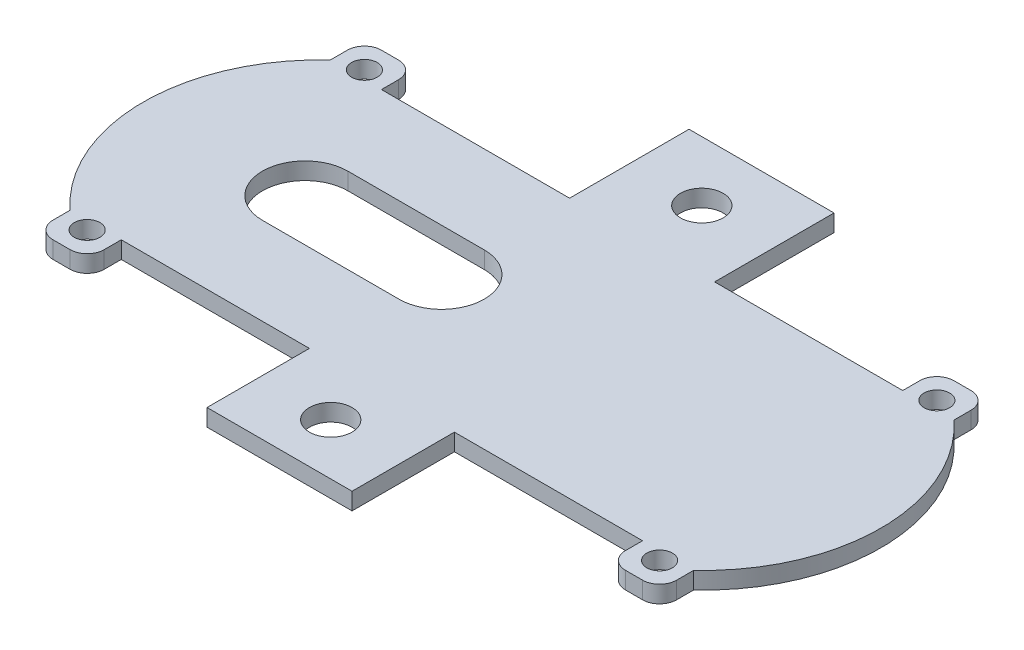
SolidWorks part; units mm, degrees
ref_plane "Front Plane" through (0, 0, 0) normal (0, 0, 1) x (1, 0, 0)
ref_plane "Top Plane" through (0, 0, 0) normal (0, 1, 0) x (1, 0, 0)
ref_plane "Right Plane" through (0, 0, 0) normal (1, 0, 0) x (0, 0, -1)
sketch "Sketch1" plane through (0, 0, 0) normal (0, 1, 0) x (1, 0, 0)
  line L0 (8.6417, -21.9202) -> (8.6417, -9.9202)
  line L1 (8.6417, -9.9202) -> (30.694, -9.9202)
  line L2 (30.694, -9.9202) -> (30.694, -13.9202)
  line L3 (30.694, -13.9202) -> (36.694, -13.9202)
  line L4 (36.694, -13.9202) -> (36.694, -9.9202)
  line L5 (36.694, 20.5798) -> (36.694, 24.5798)
  line L6 (36.694, 24.5798) -> (30.694, 24.5798)
  line L7 (30.694, 24.5798) -> (30.694, 20.5798)
  line L8 (30.694, 20.5798) -> (8.6417, 20.5798)
  line L9 (8.6417, 20.5798) -> (8.6417, 34.5798)
  line L10 (8.6417, 34.5798) -> (-8.3583, 34.5798)
  line L11 (-8.3583, 34.5798) -> (-8.3583, 20.5798)
  line L12 (-8.3583, 20.5798) -> (-30.4106, 20.5798)
  line L13 (-30.4106, 20.5798) -> (-30.4106, 24.5798)
  line L14 (-30.4106, 24.5798) -> (-36.4106, 24.5798)
  line L15 (-36.4106, 24.5798) -> (-36.4106, 20.5798)
  line L16 (-36.4106, -9.9202) -> (-36.4106, -13.9202)
  line L17 (-36.4106, -13.9202) -> (-30.4106, -13.9202)
  line L18 (-30.4106, -13.9202) -> (-30.4106, -9.9202)
  line L19 (-30.4106, -9.9202) -> (-8.3583, -9.9202)
  line L20 (-8.3583, -9.9202) -> (-8.3583, -21.9202)
  line L21 (-8.3583, -21.9202) -> (8.6417, -21.9202)
  circle A0 centre (-33.4106, 21.5798) radius 1.5
  circle A1 centre (-33.4106, -10.9202) radius 1.5
  circle A2 centre (33.694, -10.9202) radius 1.5
  circle A3 centre (33.694, 21.5798) radius 1.5
  circle A4 centre (0.1417, 28.5798) radius 3 construction
  circle A5 centre (0.1417, -15.9202) radius 3 construction
  arc A6 (36.694, -9.9202) -> (36.694, 20.5798) centre (22.6815, 5.3298) ccw
  arc A7 (-36.4106, 20.5798) -> (-36.4106, -9.9202) centre (-22.398, 5.3298) ccw
extrude "Boss-Extrude1" add sketch "Sketch1" along normal blind 2
sketch "Sketch2" plane through (0, 2, 0) normal (0, 1, 0) x (1, 0, 0)
  line L0 (-43.1083, 5.3298) -> (-40.1083, 5.3298) construction
  line L1 (-24.1083, 5.3298) -> (-8.1083, 5.3298) construction
  line L2 (-24.1083, 10.3298) -> (-8.1083, 10.3298)
  line L3 (-24.1083, 0.3298) -> (-8.1083, 0.3298)
  arc A0 (-36.4106, 20.5798) -> (-36.4106, -9.9202) centre (-22.398, 5.3298) ccw construction
  arc A1 (-24.1083, 10.3298) -> (-24.1083, 0.3298) centre (-24.1083, 5.3298) ccw
  arc A2 (-8.1083, 0.3298) -> (-8.1083, 10.3298) centre (-8.1083, 5.3298) ccw
  point P8 (-16.1083, 5.3298)
  dimension "D1" = 3
  dimension "D2" = 24
  dimension "D3" = 16
  dimension "D4" = 10
extrude "Cut-Extrude1" cut sketch "Sketch2" against normal blind 2
fillet "Fillet1" radius 2 8 edges at (-36.4106, 1, -24.5798) (-30.4106, 1, -24.5798) (-30.4106, 1, 13.9202) (-36.4106, 1, 13.9202) (30.694, 1, -24.5798) (36.694, 1, -24.5798) (30.694, 1, 13.9202) (36.694, 1, 13.9202)
sketch "Sketch3" plane through (0, 0, 0) normal (0, -1, 0) x (1, 0, 0)
  line L0 (-8.3583, -27.5798) -> (8.6417, -27.5798) construction
  line L1 (-8.3583, -34.5798) -> (-8.3583, -20.5798) construction
  line L2 (8.6417, -20.5798) -> (8.6417, -34.5798) construction
  line L3 (-8.3583, 15.9202) -> (8.6417, 15.9202) construction
  line L4 (-8.3583, 9.9202) -> (-8.3583, 21.9202) construction
  line L5 (8.6417, 21.9202) -> (8.6417, 9.9202) construction
  circle A0 centre (0.1417, -27.5798) radius 2.5
  circle A1 centre (0.1417, 15.9202) radius 2.5
  dimension "D1" = 5
  dimension "D2" = 5
extrude "Cut-Extrude2" cut sketch "Sketch3" against normal blind 10
